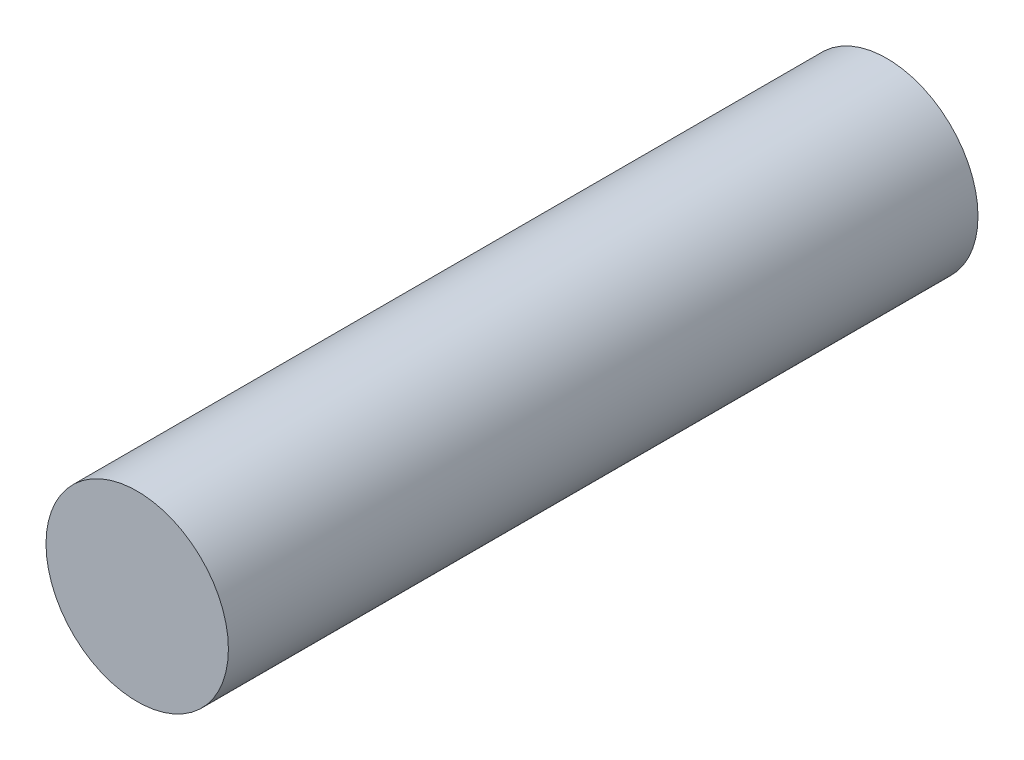
SolidWorks part; units mm, degrees
material "Paracadute"
ref_plane "Piano frontale" through (0, 0, 0) normal (0, 0, 1) x (1, 0, 0)
ref_plane "Piano superiore" through (0, 0, 0) normal (0, 1, 0) x (1, 0, 0)
ref_plane "Piano destro" through (0, 0, 0) normal (1, 0, 0) x (0, 0, -1)
sketch "Schizzo1" plane through (0, 0, 0) normal (0, 0, 1) x (1, 0, 0)
  circle A0 centre (0, 0) radius 73
  dimension "D1" = 146
extrude "Estrusione-Estrusione1" add sketch "Schizzo1" along normal blind 600
